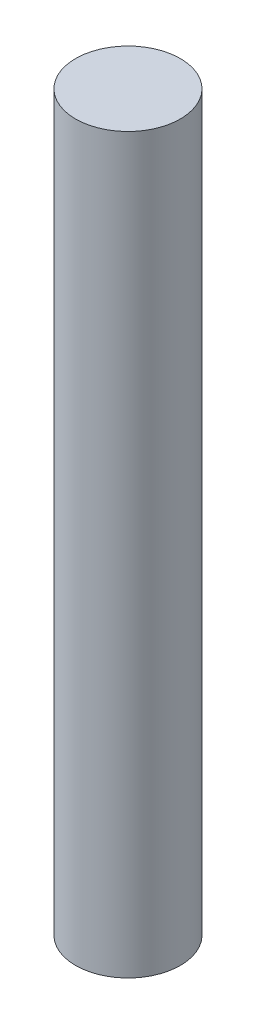
SolidWorks part; units mm, degrees
ref_plane "Front Plane" through (0, 0, 0) normal (0, 0, 1) x (1, 0, 0)
ref_plane "Top Plane" through (0, 0, 0) normal (0, 1, 0) x (1, 0, 0)
ref_plane "Right Plane" through (0, 0, 0) normal (1, 0, 0) x (0, 0, -1)
sketch "Sketch1" plane through (0, 0, 0) normal (0, 1, 0) x (1, 0, 0)
  circle A0 centre (0, 0) radius 2.5
  dimension "D1" = 5
extrude "Boss-Extrude1" add sketch "Sketch1" along normal blind 35
